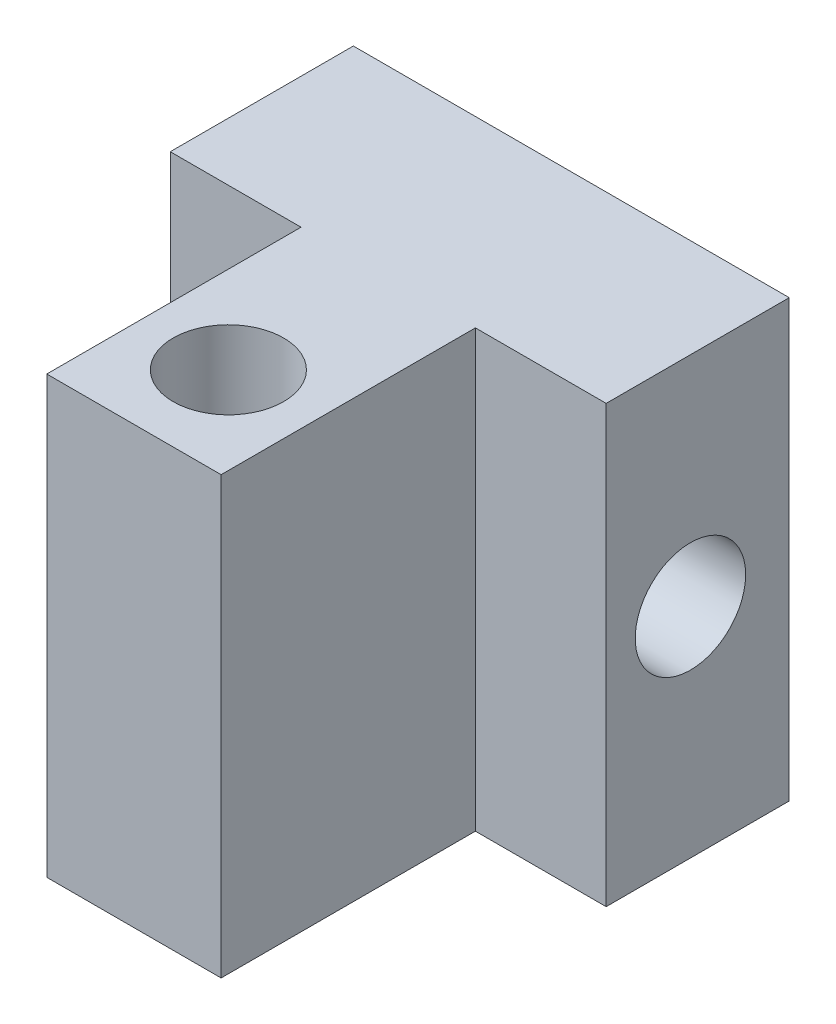
SolidWorks part; units mm, degrees
material "Lega 1060"
ref_plane "Piano frontale" through (0, 0, 0) normal (0, 0, 1) x (1, 0, 0)
ref_plane "Piano superiore" through (0, 0, 0) normal (0, 1, 0) x (1, 0, 0)
ref_plane "Piano destro" through (0, 0, 0) normal (1, 0, 0) x (0, 0, -1)
sketch "Schizzo1" plane through (0, 0, 0) normal (0, 0, 1) x (1, 0, 0)
  line L0 (-60, 0) -> (-60, 60)
  line L1 (-60, 60) -> (0, 60)
  line L6 (0, 0) -> (0, 60)
  line L7 (0, 0) -> (-60, 0)
  point P0 (0, 0)
  dimension "D1" = 60
extrude "Estrusione-Estrusione1" add sketch "Schizzo1" along normal blind 60.2
sketch "Schizzo2" plane through (0, 0, 0) normal (1, 0, 0) x (0, 0, -1)
  line L2 (-13.6, 30) -> (-47.2, 30) construction
  line L3 (-60.2, 0) -> (0, 0) construction
  line L4 (-60.2, 60) -> (0, 60) construction
  line L5 (-54.8, 30) -> (-60.2, 30) construction
  line L8 (-60.2, 0) -> (-60.2, 60) construction
  circle A0 centre (-13.6, 30) radius 7.6
  circle A1 centre (-47.2, 30) radius 7.6 construction
  dimension "D1" = 15.2
  dimension "D3" = 15.2
  dimension "D2" = 33.6
  dimension "D5" = 13
extrude "Taglio-Estrusione1" cut sketch "Schizzo2" against normal through all
sketch "Schizzo3" plane through (0, 60, 0) normal (0, 1, 0) x (0, 0, -1)
  line L0 (-47.2, 30) -> (-13.6, 30) construction
  line L3 (-60.2, 0) -> (0, 0) construction
  line L7 (-60.2, 60) -> (0, 60) construction
  line L8 (-60.2, 0) -> (-60.2, 60) construction
  circle A0 centre (-47.2, 30) radius 7.6
  circle A1 centre (-13.6, 30) radius 7.6 construction
  dimension "D1" = 15.2
  dimension "D4" = 15.2
  dimension "D2" = 13
  dimension "D3" = 33.6
extrude "Taglio-Estrusione2" cut sketch "Schizzo3" against normal through all from surface at 0 starting at face at (-30, 60, 30.1)
ref_plane "Piano3" through (0, 30, 0) normal (0, -1, 0) x (-1, 0, 0)
sketch "Schizzo4" plane through (0, 0, 60.2) normal (0, 0, 1) x (1, 0, 0)
  line L0 (-42, 60) -> (-42, 0)
  line L1 (0, 60) -> (-60, 60) construction
  line L2 (-60, 0) -> (0, 0) construction
  line L3 (-60, 60) -> (-60, 0) construction
  line L4 (-42, 60) -> (-60, 60)
  line L5 (-60, 60) -> (-60, 0)
  line L6 (-60, 0) -> (-42, 0)
  line L7 (-30, 60) -> (-30, 0) construction
  line L8 (0, 0) -> (-18, 0)
  line L9 (0, 60) -> (0, 0)
  line L10 (-18, 60) -> (0, 60)
  line L11 (-18, 60) -> (-18, 0)
  dimension "D1" = 18
extrude "Taglio-Estrusione3" cut sketch "Schizzo4" against normal blind 35
